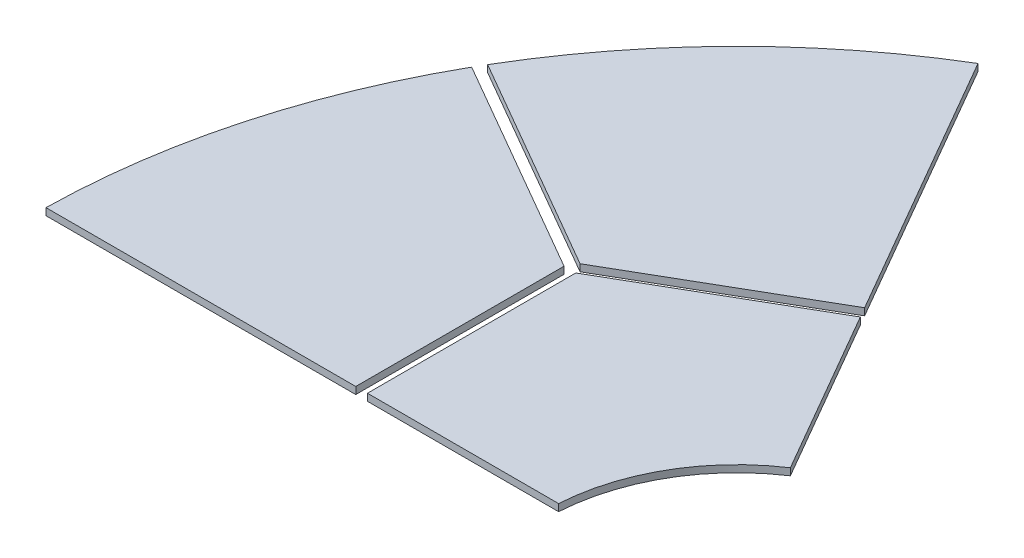
SolidWorks part; units mm, degrees
ref_plane "Front Plane" through (0, 0, 0) normal (0, 0, 1) x (1, 0, 0)
ref_plane "Top Plane" through (0, 0, 0) normal (0, 1, 0) x (1, 0, 0)
ref_plane "Right Plane" through (0, 0, 0) normal (1, 0, 0) x (0, 0, -1)
sketch "Sketch1" plane through (0, 0, 0) normal (0, 1, 0) x (1, 0, 0)
  line L0 (-152.4, 0) -> (-609.6, 0)
  line L1 (-76.2, 131.9823) -> (-304.8, 527.9291)
  line L2 (-530.4113, 300.4596) -> (-530.4291, 300.4699)
  line L3 (-525.4113, 309.1199) -> (-525.4291, 309.1301)
  line L4 (-330.2, 196.4146) -> (-516.7508, 304.1197)
  line L5 (-89.7062, 135.3756) -> (-171.2603, 276.6315)
  line L6 (-162.0918, 10) -> (-325.2, 10)
  line L7 (-176.2603, 285.2917) -> (-308.4186, 514.1966)
  line L8 (-325.2, 10) -> (-325.2, 187.7543)
  line L9 (-325.2, 187.7543) -> (-171.2603, 276.6315)
  line L10 (-335.2, 10) -> (-599.5166, 10)
  line L11 (-335.2, 10) -> (-335.2, 187.7543)
  line L12 (-330.2, 196.4146) -> (-176.2603, 285.2917)
  line L13 (-335.2, 187.7543) -> (-521.7508, 295.4594)
  line L14 (-89.7062, 135.3756) -> (-308.4186, 514.1966) construction
  line L16 (-162.0918, 10) -> (-599.5166, 10) construction
  arc A0 (-609.6, 0) -> (-304.8, 527.9291) centre (0, 0) cw
  arc A1 (-76.2, 131.9823) -> (-152.4, 0) centre (0, 0) ccw
  arc A2 (-599.5166, 10) -> (-521.7508, 295.4594) centre (0, 0) cw
  arc A3 (-89.7062, 135.3756) -> (-162.0918, 10) centre (0, 0) ccw
  arc A4 (-516.7508, 304.1197) -> (-308.4186, 514.1966) centre (0, 0) cw
  arc A6 (-599.5166, 10) -> (-308.4186, 514.1966) centre (0, 0) cw construction
  point P5 (-330.2, 0)
  point P7 (0, 0)
  point P9 (-165.1, 285.9616)
  dimension "D3" = 330.2
  dimension "D1" = 609.6
  dimension "D4" = 330.2
  dimension "D5" = 10
  dimension "D2" = 2
extrude "Boss-Extrude1" add sketch "Sketch1" along normal blind 6 contours A2 L10 L11 L13 | A4 L4 L12 L7 | A3 L5 L9 L8 L6
